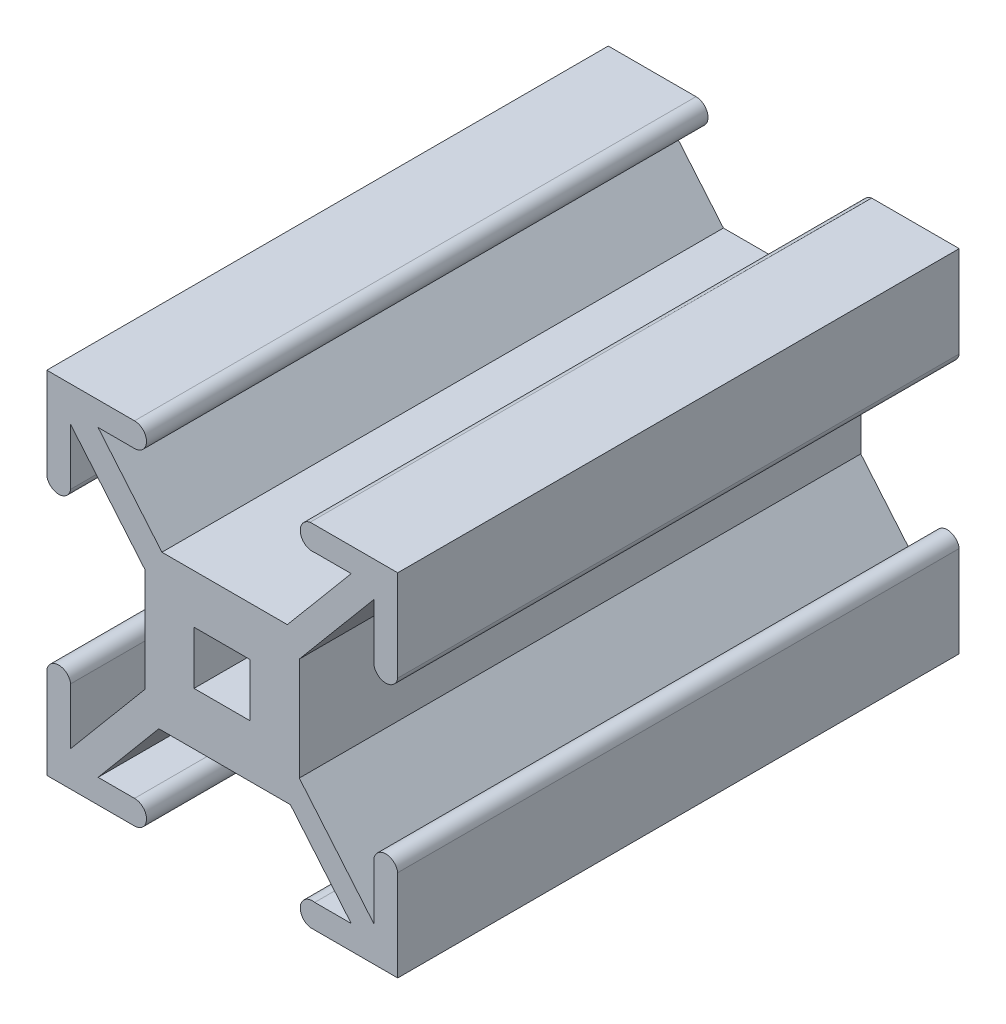
SolidWorks part; units mm, degrees
ref_plane "Front Plane" through (0, 0, 0) normal (0, 0, 1) x (1, 0, 0)
ref_plane "Top Plane" through (0, 0, 0) normal (0, 1, 0) x (1, 0, 0)
ref_plane "Right Plane" through (0, 0, 0) normal (1, 0, 0) x (0, 0, -1)
sketch "Sketch1" plane through (0, 0, 0) normal (0, 0, 1) x (1, 0, 0)
  line L1 (-21.0591, 25) -> (28.9409, 25)
  line L2 (-21.0591, 25) -> (-21.0591, -25)
  line L3 (-21.0591, -25) -> (28.9409, -25)
  line L4 (28.9409, 25) -> (28.9409, -25)
  dimension "D1" = 50
  dimension "D2" = 50
extrude "Boss-Extrude1" add sketch "Sketch1" along normal blind 80
sketch "Sketch2" plane through (0, 0, 0) normal (0, 0, -1) x (-1, 0, 0)
  line L1 (-12.9409, 9) -> (5.0591, 9)
  line L2 (-12.9409, 9) -> (-12.9409, -9)
  line L3 (-12.9409, -9) -> (5.0591, -9)
  line L4 (5.0591, 9) -> (5.0591, -9)
  line L8 (-28.9409, -25) -> (-28.9409, 25) construction
  line L9 (21.0591, 25) -> (21.0591, -25) construction
  line L10 (21.0591, -25) -> (-28.9409, -25) construction
  line L11 (-28.9409, 25) -> (21.0591, 25) construction
  dimension "D1" = 16
  dimension "D2" = 16
  dimension "D3" = 16
  dimension "D4" = 16
extrude "Cut-Extrude2" cut sketch "Sketch2" against normal blind 287
sketch "Sketch3" plane through (0, 0, 0) normal (0, 0, -1) x (-1, 0, 0)
  line L1 (-22.3163, 21.5842) -> (-17.1163, 21.5842)
  line L9 (-28.9409, 25) -> (-16.4651, 25)
  line L10 (-28.9409, 25) -> (21.0591, 25) construction
  line L11 (-17.2817, 15.5842) -> (-22.3163, 21.5842)
  line L12 (-28.9409, 25) -> (-28.9409, 12.5)
  line L13 (-28.9409, -25) -> (-28.9409, 25) construction
  line L15 (8.7183, 15.5842) -> (13.7529, 21.5842)
  line L16 (13.7529, 21.5842) -> (8.5591, 21.5842)
  line L17 (-25.5409, 20.0034) -> (-18.5395, 11.6595)
  line L18 (8.5591, 25) -> (21.0591, 25)
  line L19 (-25.5409, 20.0034) -> (-25.5409, 12.0034)
  line L20 (10.6577, 11.6595) -> (7.0357, 7.3429)
  line L21 (17.6591, 20.0034) -> (10.6577, 11.6595)
  line L22 (17.6591, 20.0034) -> (17.6591, 12.0034)
  line L23 (21.0591, 25) -> (21.0591, 12.5)
  line L24 (-18.5395, 11.6595) -> (-14.9175, 7.3429)
  line L26 (-25.5409, -20.0034) -> (-18.5395, -11.6595)
  line L27 (-25.5409, -20.0034) -> (-25.5409, -12.0034)
  line L28 (-28.9409, -25) -> (-28.9409, -12.5)
  line L29 (-28.9409, -25) -> (-16.4651, -25)
  line L30 (-22.3163, -21.5842) -> (-17.1163, -21.5842)
  line L31 (-17.2817, -15.5842) -> (-22.3163, -21.5842)
  line L32 (17.6591, -20.0034) -> (10.6577, -11.6595)
  line L33 (17.6591, -20.0034) -> (17.6591, -12.0034)
  line L34 (21.0591, -25) -> (21.0591, -12.5)
  line L35 (8.5591, -25) -> (21.0591, -25)
  line L36 (13.7529, -21.5842) -> (8.5591, -21.5842)
  line L37 (8.7183, -15.5842) -> (13.7529, -21.5842)
  line L40 (-13.217, 10.7401) -> (4.6536, 10.7401)
  line L41 (-14.9175, 7.3429) -> (-14.9175, -7.3429)
  line L42 (-13.6531, -11.2599) -> (5.0898, -11.2599)
  line L43 (7.0357, 7.3429) -> (7.0357, -7.3429)
  line L44 (-14.9175, 10.7401) -> (7.0357, -11.2599) construction
  line L45 (-14.9175, -11.2599) -> (7.0357, 10.7401) construction
  line L46 (-17.2817, 15.5842) -> (-13.217, 10.7401)
  line L47 (8.7183, 15.5842) -> (4.6536, 10.7401)
  line L48 (8.7183, -15.5842) -> (5.0898, -11.2599)
  line L49 (-18.5395, -11.6595) -> (-14.9175, -7.3429)
  line L50 (-17.2817, -15.5842) -> (-13.6531, -11.2599)
  line L51 (10.6577, -11.6595) -> (7.0357, -7.3429)
  arc A0 (8.5591, 21.5842) -> (8.5591, 25) centre (8.5591, 23.2921) cw
  arc A1 (-16.4651, 25) -> (-17.1163, 21.5842) centre (-16.7907, 23.2921) cw
  arc A2 (-25.5409, 12.0034) -> (-28.9409, 12.5) centre (-27.2409, 12.2517) cw
  arc A3 (17.6591, 12.0034) -> (21.0591, 12.5) centre (19.3591, 12.2517) ccw
  arc A4 (-25.5409, -12.0034) -> (-28.9409, -12.5) centre (-27.2409, -12.2517) ccw
  arc A5 (-16.4651, -25) -> (-17.1163, -21.5842) centre (-16.7907, -23.2921) ccw
  arc A6 (17.6591, -12.0034) -> (21.0591, -12.5) centre (19.3591, -12.2517) cw
  arc A7 (8.5591, -21.5842) -> (8.5591, -25) centre (8.5591, -23.2921) ccw
  point P23 (-3.9409, -0.2599)
extrude "Cut-Extrude5" cut sketch "Sketch3" against normal blind 287 flip side to cut
sketch "Sketch4" plane through (0, 0, 0) normal (0, 0, -1) x (-1, 0, 0)
  line L1 (-12.9409, 9) -> (5.0591, 9)
  line L2 (-12.9409, 9) -> (-12.9409, -9)
  line L3 (-12.9409, -9) -> (5.0591, -9)
  line L4 (5.0591, 9) -> (5.0591, -9)
extrude "Boss-Extrude2" add sketch "Sketch4" against normal blind 80
sketch "Sketch5" plane through (0, 0, 0) normal (0, 0, -1) x (-1, 0, 0)
  line L1 (-7.9175, 3.7766) -> (0.0825, 3.7766)
  line L2 (-7.9175, 3.7766) -> (-7.9175, -3.7766)
  line L3 (-7.9175, -3.7766) -> (0.0825, -3.7766)
  line L4 (0.0825, 3.7766) -> (0.0825, -3.7766)
  line L5 (-7.9175, 3.7766) -> (0.0825, -3.7766) construction
  line L6 (-7.9175, -3.7766) -> (0.0825, 3.7766) construction
  point P0 (-3.9175, 0)
extrude "Cut-Extrude6" cut sketch "Sketch5" against normal blind 250
